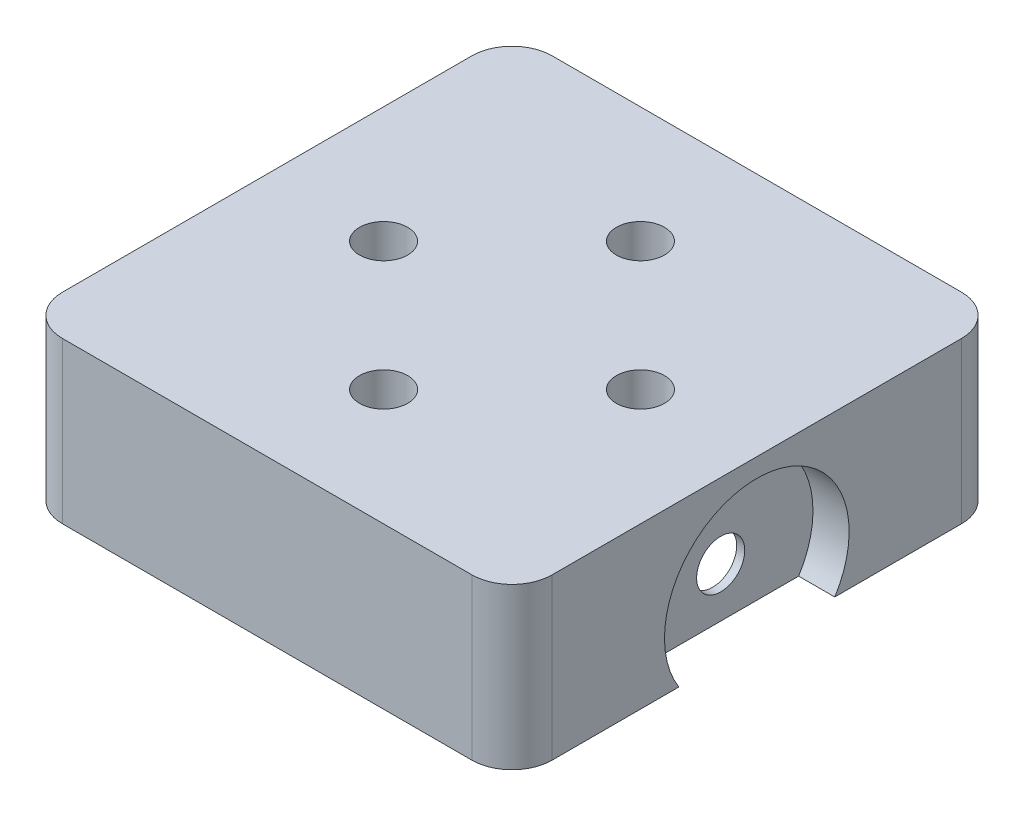
SolidWorks part; units mm, degrees
ref_plane "Front Plane" through (0, 0, 0) normal (0, 0, 1) x (1, 0, 0)
ref_plane "Top Plane" through (0, 0, 0) normal (0, 1, 0) x (1, 0, 0)
ref_plane "Right Plane" through (0, 0, 0) normal (1, 0, 0) x (0, 0, -1)
sketch "Sketch1" plane through (0, 0, 0) normal (0, 1, 0) x (1, 0, 0)
  line L1 (-220, 270) -> (220, 270)
  line L2 (-270, 220) -> (-270, -220)
  line L3 (-220, -270) -> (220, -270)
  line L4 (270, 220) -> (270, -220)
  line L5 (-270, 270) -> (270, -270) construction
  line L6 (-270, -270) -> (270, 270) construction
  arc A0 (220, 270) -> (270, 220) centre (220, 220) cw
  arc A1 (220, -270) -> (270, -220) centre (220, -220) ccw
  arc A2 (-220, -270) -> (-270, -220) centre (-220, -220) cw
  arc A3 (-270, 220) -> (-220, 270) centre (-220, 220) cw
  point P4 (0, 0)
  dimension "D3" = 50
  dimension "D1" = 540
  dimension "D2" = 540
extrude "Boss-Extrude1" add sketch "Sketch1" along normal blind 200
ref_plane "Plane1" through (0, 200, 0) normal (0, 1, 0) x (1, 0, 0)
sketch "Sketch4" plane through (0, 200, 0) normal (0, 1, 0) x (1, 0, 0)
  circle A0 centre (0, 160) radius 30
  circle A1 centre (160, 0) radius 30
  circle A2 centre (0, -160) radius 30
  circle A3 centre (-160, 0) radius 30
  dimension "D2" = 60
  dimension "D1" = 160
  dimension "D3" = 4
extrude "Cut-Extrude1" cut sketch "Sketch4" against normal blind 60
shell "Shell1" thickness 20
ref_plane "Plane2" through (310, 0, 0) normal (1, 0, 0) x (0, 0, -1)
sketch "Sketch5" plane through (0, 0, 0) normal (0, 1, 0) x (1, 0, 0)
  line L0 (-220, 270) -> (220, 270)
  line L1 (-255, 305) -> (255, 305)
  line L2 (-305, 255) -> (-305, -255)
  line L3 (-255, -305) -> (255, -305)
  line L4 (305, 255) -> (305, -255)
  line L5 (-305, 305) -> (-290.3553, 290.3553) construction
  line L6 (-305, -305) -> (-290.3553, -290.3553) construction
  line L7 (270, 220) -> (270, -220)
  line L8 (220, -270) -> (-220, -270)
  line L9 (-270, -220) -> (-270, 220)
  line L12 (-270, -270) -> (270, 270) construction
  line L13 (-270, 270) -> (270, -270) construction
  line L14 (290.3553, 290.3553) -> (305, 305) construction
  line L15 (290.3553, -290.3553) -> (305, -305) construction
  arc A0 (255, 305) -> (305, 255) centre (255, 255) cw
  arc A1 (255, -305) -> (305, -255) centre (255, -255) ccw
  arc A2 (-255, -305) -> (-305, -255) centre (-255, -255) cw
  arc A3 (-305, 255) -> (-255, 305) centre (-255, 255) cw
  arc A4 (270, 220) -> (220, 270) centre (220, 220) ccw
  arc A5 (-220, -270) -> (-270, -220) centre (-220, -220) cw
  arc A6 (-270, 220) -> (-220, 270) centre (-220, 220) cw
  arc A7 (220, -270) -> (270, -220) centre (220, -220) ccw
  point P4 (0, 0)
  point P32 (270, 285.3553)
  point P33 (270, -280.388)
  point P34 (-270, 285.3553)
  point P35 (-270, -280.388)
  dimension "D3" = 50
  dimension "D4" = 50
  dimension "D1" = 610
  dimension "D2" = 610
extrude "Boss-Extrude2" add sketch "Sketch5" along normal blind 200
sketch "Sketch6" plane through (310, 0, 0) normal (1, 0, 0) x (0, 0, -1)
  circle A0 centre (0, 61.5687) radius 115
  dimension "D1" = 230
extrude "Cut-Extrude3" cut sketch "Sketch6" against normal blind 50
ref_plane "Plane3" through (310, 0, 0) normal (1, 0, 0) x (0, 0, -1)
sketch "Sketch7" plane through (310, 0, 0) normal (1, 0, 0) x (0, 0, -1)
  circle A0 centre (0, 61.5687) radius 30
  dimension "D1" = 60
extrude "Cut-Extrude4" cut sketch "Sketch7" against normal through all both and the other way through all contours A0
ref_plane "Plane4" through (0, 0, 0) normal (1, 0, 0) x (0, 0, -1)
mirror "Mirror1" about plane through (0, 0, 0) normal (1, 0, 0) of "Cut-Extrude3"
